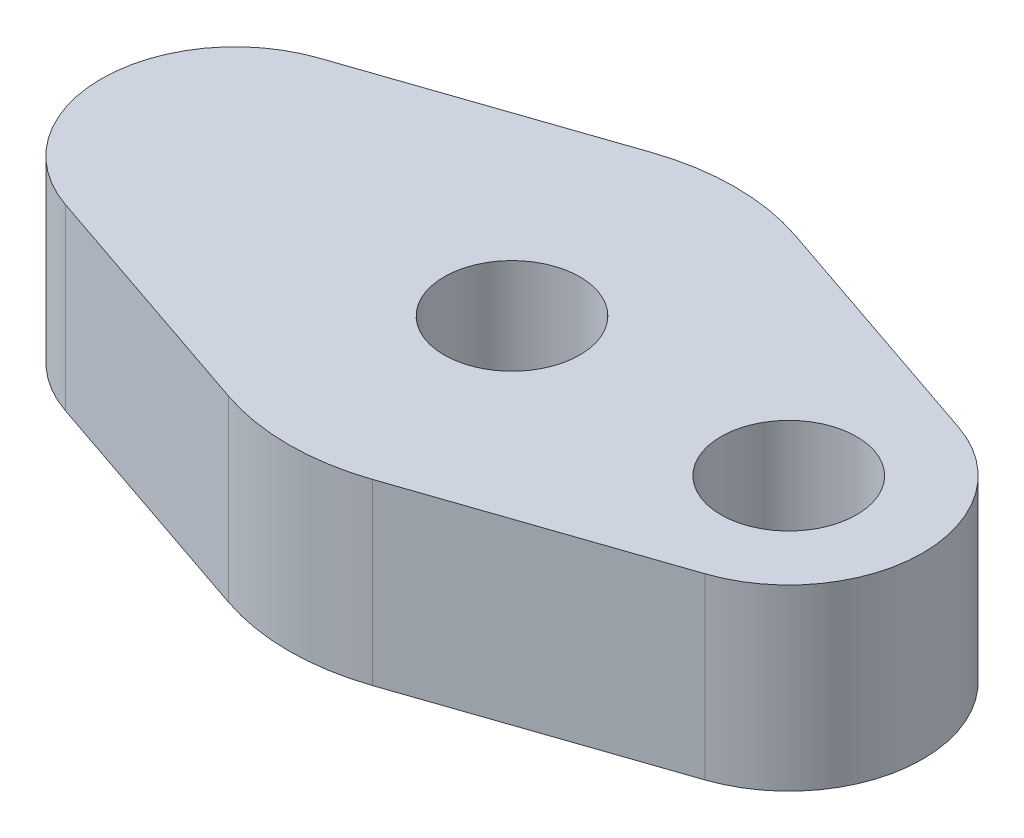
SolidWorks part; units mm, degrees
ref_plane "Front Plane" through (0, 0, 0) normal (0, 0, 1) x (1, 0, 0)
ref_plane "Top Plane" through (0, 0, 0) normal (0, 1, 0) x (1, 0, 0)
ref_plane "Right Plane" through (0, 0, 0) normal (1, 0, 0) x (0, 0, -1)
sketch "Sketch1" plane through (0, 0, 0) normal (0, 1, 0) x (1, 0, 0)
  line L0 (-8.9597, 3.5495) -> (-2.0161, 5.9159)
  line L1 (-8.9597, -3.5495) -> (-2.0161, -5.9159)
  line L2 (2.0161, 5.9159) -> (8.9597, 3.5495)
  line L3 (8.9597, -3.5495) -> (2.0161, -5.9159)
  circle A0 centre (0, 0) radius 4 construction
  circle A1 centre (0, 0) radius 6.25
  circle A2 centre (7.75, 0) radius 2.5 construction
  circle A3 centre (-7.75, 0) radius 2.5 construction
  circle A4 centre (-7.75, 0) radius 3.75
  circle A5 centre (7.75, 0) radius 3.75
  dimension "D1" = 7.5
  dimension "D2" = 8
  dimension "D3" = 12.5
  dimension "D4" = 5
extrude "Boss-Extrude1" add sketch "Sketch1" along normal blind 5 contours A1 A4 A3 | A1 A4 A3 | A5 A1 A4 | A4 L1 A1 | A5 A1 L3 | A1 A5 A2 | A5 A1 A2 | A5 L2 A1 | A4 A1 L0
sketch "Sketch2" plane through (0, 5, 0) normal (0, 1, 0) x (1, 0, 0)
  line L0 (0, -6.25) -> (0, 6.25) construction
  line L1 (11.5, 0) -> (-11.5, 0) construction
  arc A0 (-2.0161, -5.9159) -> (2.0161, -5.9159) centre (0, 0) ccw construction
  arc A1 (2.0161, 5.9159) -> (-2.0161, 5.9159) centre (0, 0) ccw construction
  arc A2 (8.9597, -3.5495) -> (8.9597, 3.5495) centre (7.75, 0) ccw construction
  arc A3 (-8.9597, 3.5495) -> (-8.9597, -3.5495) centre (-7.75, 0) ccw construction
  circle A4 centre (0, 0) radius 4
extrude "Boss-Extrude2" [suppressed] add sketch "Sketch2" along normal blind 22.5
sketch "Sketch3" [suppressed] plane through (0, 27.5, 0) normal (0, 1, 0) x (1, 0, 0)
  circle A0 centre (0, 0) radius 3
  dimension "D1" = 6
extrude "Boss-Extrude3" [suppressed] add sketch "Sketch3" along normal blind 2
sketch "Sketch4" [suppressed] plane through (0, 29.5, 0) normal (0, 1, 0) x (1, 0, 0)
  circle A0 centre (0, 0) radius 4
extrude "Boss-Extrude4" [suppressed] add sketch "Sketch4" along normal blind 2
hole_wizard "#6 Clearance Hole1" positions "Sketch5" profile "Sketch6" hole size "#6" standard "ANSI Inch" end condition through all
sketch "Sketch5" plane through (0, 5, 0) normal (0, 1, 0) x (1, 0, 0)
  point P3 (7.75, 0)
  point P6 (0, 0)
sketch "Sketch6" plane through (7.75, 5, 0) normal (1, 0, 0) x (0, 0, 1)
  line L0 (0, 0) -> (0, 5)
  line L1 (0, 5) -> (1.8986, 5)
  line L2 (1.8986, 5) -> (1.8986, 0)
  line L5 (1.8986, 0) -> (0, 0)
  line L11 (0, -6.35) -> (0, 107.95) construction
  dimension "Thru Hole Dia." = 3.7973
  dimension "Thru Hole Depth" = 5
